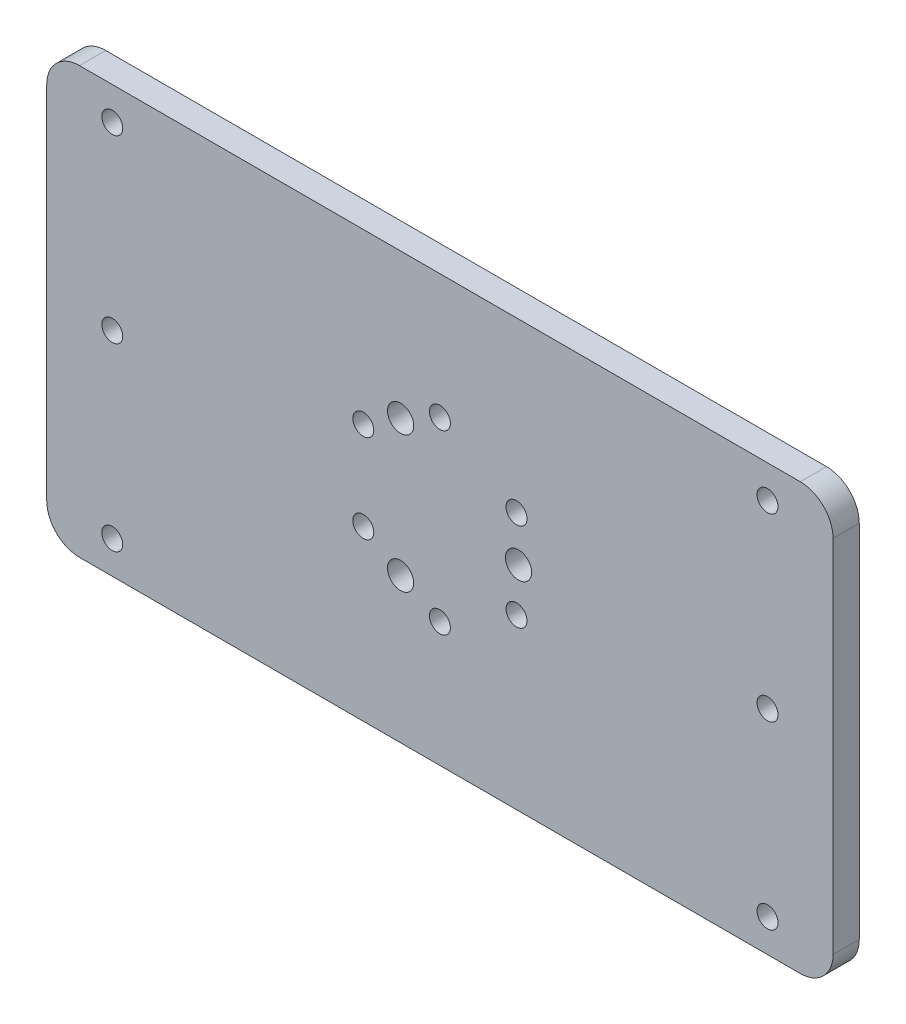
SolidWorks part; units mm, degrees
ref_plane "前视基准面" through (0, 0, 0) normal (0, 0, 1) x (1, 0, 0)
ref_plane "上视基准面" through (0, 0, 0) normal (0, 1, 0) x (1, 0, 0)
ref_plane "右视基准面" through (0, 0, 0) normal (1, 0, 0) x (0, 0, -1)
other "Configuration Table"
sketch "草图1" plane through (0, 0, 0) normal (0, 0, 1) x (1, 0, 0)
  line L1 (0, 0) -> (120, 0)
  line L2 (0, 0) -> (0, -65)
  line L3 (0, -65) -> (120, -65)
  line L4 (120, 0) -> (120, -65)
  dimension "D1" = 65
  dimension "D2" = 120
extrude "凸台-拉伸1" add sketch "草图1" along normal blind 4
sketch "草图2" plane through (0, 0, 4) normal (0, 0, 1) x (1, 0, 0)
  line L0 (10, 0) -> (10, -65) construction
  line L1 (120, 0) -> (0, 0) construction
  line L2 (0, -65) -> (120, -65) construction
  line L3 (0, 0) -> (0, -65) construction
  line L4 (60, 0) -> (60, -65) construction
  line L5 (110, 0) -> (110, -65) construction
  circle A0 centre (10, -5) radius 1.6
  circle A1 centre (10, -32.5) radius 1.6
  circle A2 centre (10, -60) radius 1.6
  circle A3 centre (110, -60) radius 1.6
  circle A4 centre (110, -32.5) radius 1.6
  circle A5 centre (110, -5) radius 1.6
  dimension "D2" = 3.2
  dimension "D3" = 5
  dimension "D4" = 5
  dimension "D1" = 10
extrude "切除-拉伸1" cut sketch "草图2" against normal through all
fillet "圆角1" radius 5 4 edges at (120, 0, 2) (120, -65, 2) (0, -65, 2) (0, 0, 2)
sketch "草图4" plane through (0, 0, 4) normal (0, 0, 1) x (1, 0, 0)
  line L0 (10, -32.5) -> (110, -32.5) construction
  circle A0 centre (60, -32.5) radius 13.5 construction
  circle A1 centre (60, -32.5) radius 12 construction
  circle A2 centre (72, -32.5) radius 2
  circle A3 centre (60, -19) radius 1.6
  circle A4 centre (71.6913, -25.75) radius 1.6
  circle A5 centre (71.6913, -39.25) radius 1.6
  circle A6 centre (60, -46) radius 1.6
  circle A7 centre (48.3087, -39.25) radius 1.6
  circle A8 centre (48.3087, -25.75) radius 1.6
  circle A9 centre (54, -42.8923) radius 2
  circle A10 centre (54, -22.1077) radius 2
  dimension "D1" = 27
  dimension "D2" = 24
  dimension "D3" = 4
  dimension "D4" = 3.2
  dimension "D5" = 6
  dimension "D6" = 3
extrude "切除-拉伸3" cut sketch "草图4" against normal blind 12.5
